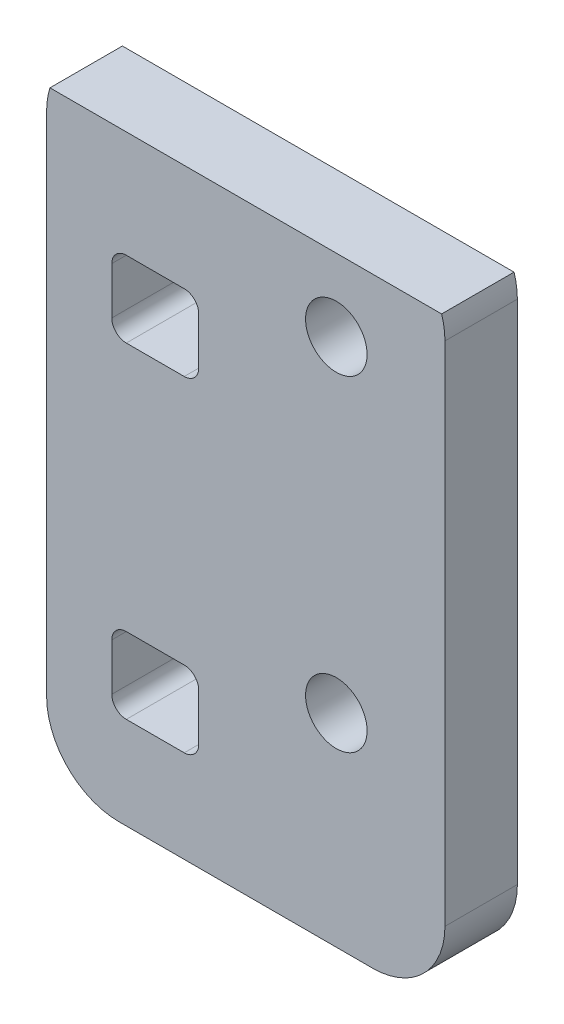
SolidWorks part; units mm, degrees
ref_plane "Front Plane" through (0, 0, 0) normal (0, 0, 1) x (1, 0, 0)
ref_plane "Top Plane" through (0, 0, 0) normal (0, 1, 0) x (1, 0, 0)
ref_plane "Right Plane" through (0, 0, 0) normal (1, 0, 0) x (0, 0, -1)
sketch "Sketch2" plane through (0, 0, 0) normal (0, 0, 1) x (1, 0, 0)
  line L0 (34, 243.5706) -> (34, 233.0706) construction
  line L1 (74, 310.3206) -> (174, 310.3206) construction
  line L2 (74, 310.3206) -> (74, 220.3206) construction
  line L3 (74, 220.3206) -> (174, 220.3206) construction
  line L4 (174, 310.3206) -> (174, 220.3206) construction
  line L5 (28, 238.3206) -> (40, 238.3206) construction
  line L8 (74, 310.3206) -> (19, 310.3206)
  line L9 (74, 310.3206) -> (74, 220.3206)
  line L10 (74, 220.3206) -> (19, 220.3206)
  line L11 (19, 310.3206) -> (19, 220.3206)
  line L13 (30, 278.0706) -> (38, 278.0706)
  line L14 (28, 280.0706) -> (28, 286.5706)
  line L15 (30, 288.5706) -> (38, 288.5706)
  line L16 (40, 280.0706) -> (40, 286.5706)
  line L17 (28, 278.0706) -> (40, 288.5706) construction
  line L18 (28, 288.5706) -> (40, 278.0706) construction
  line L22 (30, 233.0706) -> (38, 233.0706)
  line L23 (40, 241.5706) -> (40, 235.0706)
  line L24 (30, 243.5706) -> (38, 243.5706)
  line L25 (28, 241.5706) -> (28, 235.0706)
  circle A0 centre (59, 293.3206) radius 15
  circle A1 centre (59, 293.3206) radius 4.25
  arc A2 (30, 278.0706) -> (28, 280.0706) centre (30, 280.0706) cw
  arc A3 (38, 278.0706) -> (40, 280.0706) centre (38, 280.0706) ccw
  arc A4 (38, 288.5706) -> (40, 286.5706) centre (38, 286.5706) cw
  arc A5 (28, 286.5706) -> (30, 288.5706) centre (30, 286.5706) cw
  circle A11 centre (59, 248.3206) radius 4.25
  arc A12 (38, 233.0706) -> (40, 235.0706) centre (38, 235.0706) ccw
  arc A13 (38, 243.5706) -> (40, 241.5706) centre (38, 241.5706) cw
  arc A14 (30, 243.5706) -> (28, 241.5706) centre (30, 241.5706) ccw
  arc A15 (28, 235.0706) -> (30, 233.0706) centre (30, 235.0706) ccw
  point P17 (34, 283.3206)
  point P44 (34, 238.3206)
  dimension "D4" = 30
  dimension "D7" = 8.5
  dimension "D10" = 2
  dimension "D1" = 100
  dimension "D2" = 90
  dimension "D3" = 55
  dimension "D5" = 17
  dimension "D6" = 15
  dimension "D8" = 10.5
  dimension "D9" = 12
  dimension "D11" = 45
  dimension "D12" = 15
extrude "Boss-Extrude1" add sketch "Sketch2" along normal blind 10
fillet "Fillet1" radius 10 4 edges at (74, 220.3206, 5) (19, 220.3206, 5) (74, 310.3206, 5) (19, 310.3206, 5)
sketch "Sketch3" plane through (0, 0, 10) normal (0, 0, 1) x (1, 0, 0)
  line L0 (34, 233.0706) -> (34, 243.5706) construction
  line L1 (30, 233.0706) -> (38, 233.0706) construction
  line L2 (30, 243.5706) -> (38, 243.5706) construction
  line L3 (40, 238.3206) -> (28, 238.3206) construction
  line L4 (40, 241.5706) -> (40, 235.0706) construction
  line L5 (28, 241.5706) -> (28, 235.0706) construction
  line L6 (34, 238.3206) -> (34, 283.3206) construction
extrude "Cut-Extrude1" cut sketch "Sketch4" against normal blind 600
sketch "Sketch4" plane through (-127, 1084.7977, -1205.1099) normal (-1, 0, 0) x (0, 1, 0)
  line L1 (-781.4771, -1215.2099) -> (-501.4771, -1215.2099)
  line L2 (-781.4771, -1215.2099) -> (-781.4771, -743.2099)
  line L3 (-781.4771, -743.2099) -> (-501.4771, -743.2099)
  line L4 (-501.4771, -1215.2099) -> (-501.4771, -743.2099)
  line L5 (-781.4771, -1215.2099) -> (-501.4771, -743.2099) construction
  line L6 (-781.4771, -743.2099) -> (-501.4771, -1215.2099) construction
  line L10 (-206.4771, -743.2099) -> (-96.4771, -743.2099)
  line L11 (-216.4771, -753.2099) -> (-216.4771, -1205.2099)
  line L12 (-206.4771, -1215.2099) -> (-96.4771, -1215.2099)
  line L13 (-86.4771, -753.2099) -> (-86.4771, -1205.2099)
  arc A0 (-96.4771, -743.2099) -> (-86.4771, -753.2099) centre (-96.4771, -753.2099) cw
  arc A1 (-206.4771, -743.2099) -> (-216.4771, -753.2099) centre (-206.4771, -753.2099) ccw
  arc A2 (-96.4771, -1215.2099) -> (-86.4771, -1205.2099) centre (-96.4771, -1205.2099) ccw
  arc A3 (-216.4771, -1205.2099) -> (-206.4771, -1215.2099) centre (-206.4771, -1205.2099) ccw
  point P0 (-641.4771, -979.2099)
  point P21 (-86.4771, -743.2099)
  point P24 (-216.4771, -743.2099)
  point P27 (-86.4771, -1215.2099)
